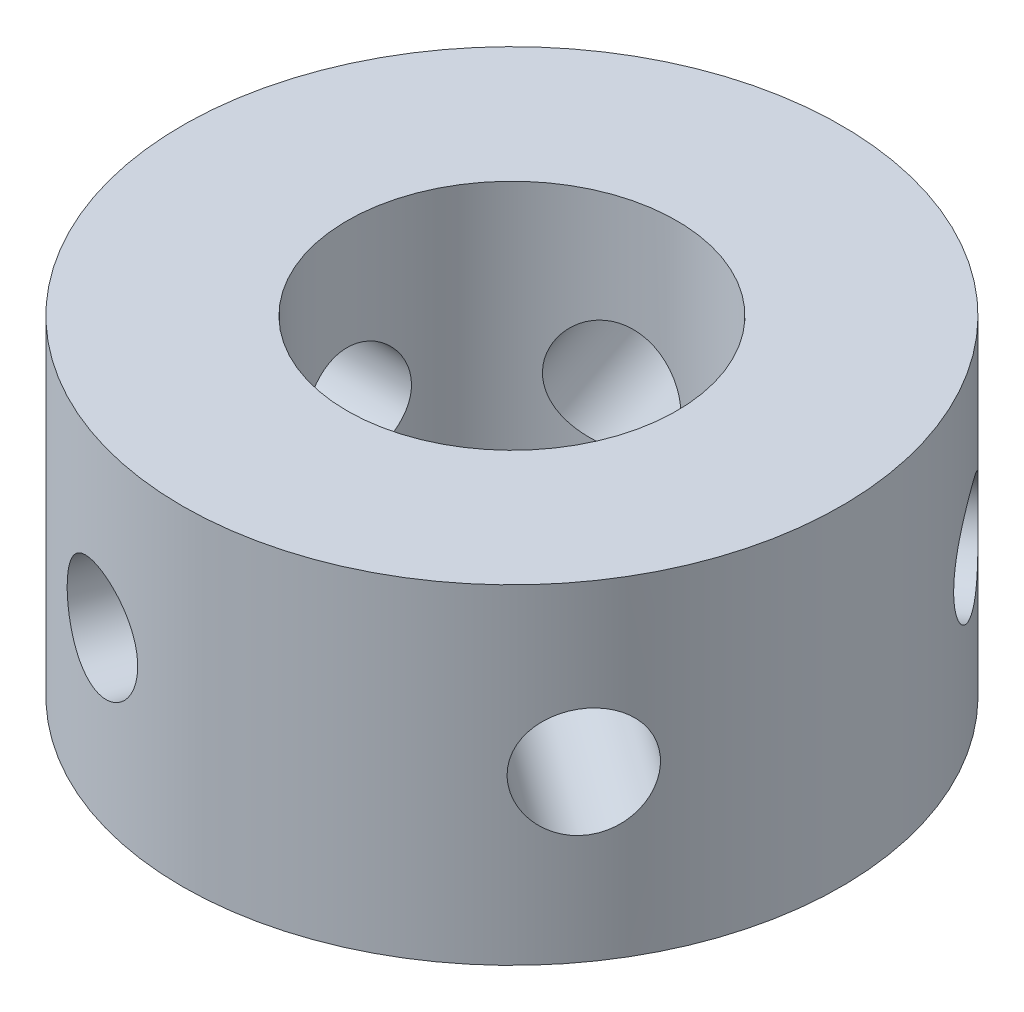
SolidWorks part; units mm, degrees
ref_plane "Front Plane" through (0, 0, 0) normal (0, 0, 1) x (1, 0, 0)
ref_plane "Top Plane" through (0, 0, 0) normal (0, 1, 0) x (1, 0, 0)
ref_plane "Right Plane" through (0, 0, 0) normal (1, 0, 0) x (0, 0, -1)
sketch "Sketch1" plane through (0, 0, 0) normal (0, 1, 0) x (1, 0, 0)
  circle A0 centre (0, 0) radius 1.5
  circle A1 centre (0, 0) radius 3
  dimension "D1" = 3
  dimension "D2" = 6
extrude "Boss-Extrude1" add sketch "Sketch1" along normal blind 3
sketch "Sketch2" plane through (0, 0, 0) normal (1, 0, 0) x (0, 0, -1)
  line L0 (0, 0) -> (0, 3)
  line L1 (3, 3) -> (-3, 3) construction
  circle A0 centre (0, 1.5) radius 0.5
  dimension "D1" = 1
extrude "Cut-Extrude1" cut sketch "Sketch2" against normal blind 3 contours L0 A0 | L0 A0
sketch "Sketch3" plane through (0, 0, 0) normal (1, 0, 0) x (0, 0, -1)
  line L0 (0, 0) -> (0, 3.4429)
pattern_circular "CirPattern1" count 5 every 72 about axis through (0, 0, 0) along (0, 1, 0) of "Cut-Extrude1"
